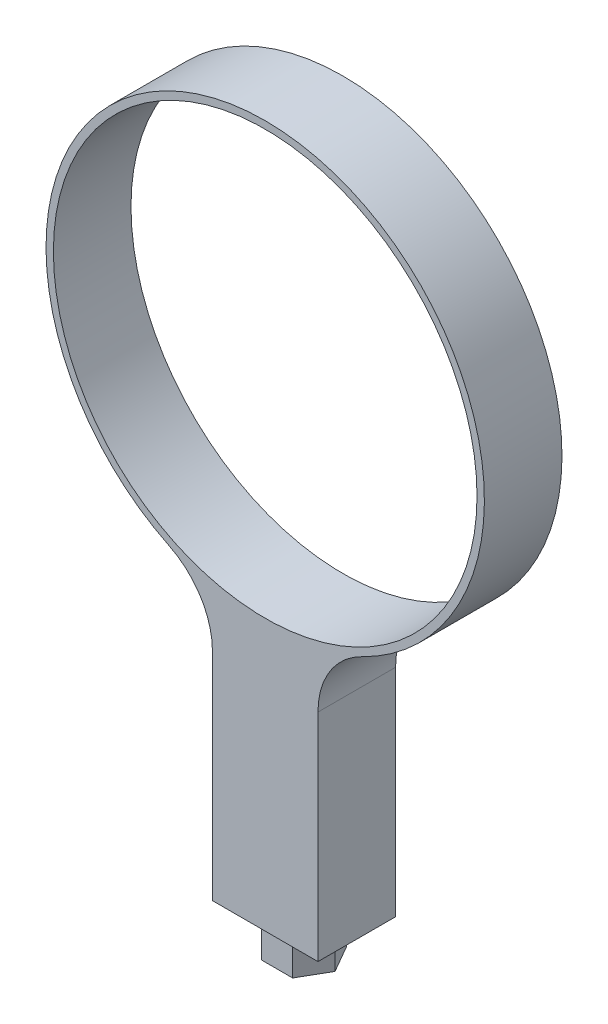
SolidWorks part; units mm, degrees
ref_plane "Front Plane" through (0, 0, 0) normal (0, 0, 1) x (1, 0, 0)
ref_plane "Top Plane" through (0, 0, 0) normal (0, 1, 0) x (1, 0, 0)
ref_plane "Right Plane" through (0, 0, 0) normal (1, 0, 0) x (0, 0, -1)
sketch "Sketch1" plane through (0, 0, 0) normal (0, 0, 1) x (1, 0, 0)
  line L0 (-13.6, -124.4259) -> (13.6, -124.4259)
  line L2 (-13.6, -124.4259) -> (-13.6, -68.7262)
  line L4 (13.6, -124.4259) -> (13.6, -68.7262)
  line L8 (13.6, -124.4259) -> (13.6, -68.7262)
  circle A0 centre (0, 0) radius 54.6
  arc A1 (24.8157, -50.7586) -> (-24.8157, -50.7586) centre (0, 0) ccw
  arc A2 (-13.6, -68.7262) -> (-24.8157, -50.7586) centre (-33.6, -68.7262) ccw
  arc A3 (24.8157, -50.7586) -> (13.6, -68.7262) centre (33.6, -68.7262) ccw
  dimension "D1" = 109.2
  dimension "D2" = 113
  dimension "D3" = 20
  dimension "D4" = 20
extrude "Boss-Extrude1" add sketch "Sketch1" along normal blind 20 contours A3 A1 A2 L2 L0 L4 A0
sketch "Sketch3" plane through (0, -124.4259, 0) normal (0, -1, 0) x (-1, 0, 0)
  line L0 (13.6, -20) -> (-13.6, 0)
  line L1 (13.6, -20) -> (-13.6, -20)
  line L2 (13.6, -20) -> (13.6, 0)
  line L3 (13.6, 0) -> (-13.6, 0)
  line L4 (-13.6, -20) -> (-13.6, 0)
  line L5 (13.6, 0) -> (-13.6, -20)
  line L7 (-4, -16.9282) -> (4, -16.9282)
  line L8 (4, -16.9282) -> (8, -10)
  line L9 (8, -10) -> (4, -3.0718)
  line L10 (4, -3.0718) -> (-4, -3.0718)
  line L11 (-4, -3.0718) -> (-8, -10)
  line L12 (-8, -10) -> (-4, -16.9282)
  circle A0 centre (0, -10) radius 6.9282 construction
  dimension "D1" = 8
extrude "Boss-Extrude2" add sketch "Sketch3" along normal blind 10 contours L5 L12 L7 L8 L0 | L11 L12 L5 L0 | L10 L11 L0 L5 L9 | L8 L9 L5 L0
